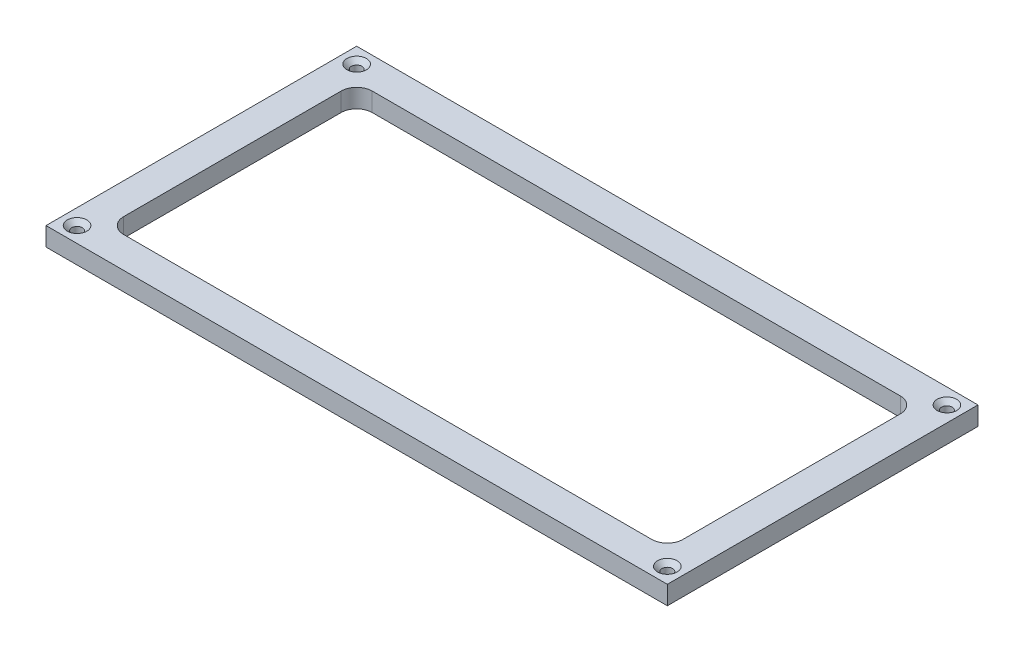
SolidWorks part; units mm, degrees
material "Pine"
ref_plane "Front Plane" through (0, 0, 0) normal (0, 0, 1) x (1, 0, 0)
ref_plane "Top Plane" through (0, 0, 0) normal (0, 1, 0) x (1, 0, 0)
ref_plane "Right Plane" through (0, 0, 0) normal (1, 0, 0) x (0, 0, -1)
sketch "Sketch1" plane through (0, 0, 0) normal (0, 1, 0) x (1, 0, 0)
  line L1 (0, 0) -> (200, 0)
  line L2 (0, 0) -> (0, 100)
  line L3 (0, 100) -> (200, 100)
  line L4 (200, 0) -> (200, 100)
  dimension "D1" = 200
  dimension "D2" = 100
extrude "Boss-Extrude1" add sketch "Sketch1" along normal blind 6
sketch "Sketch2" plane through (0, 6, 0) normal (0, 1, 0) x (1, 0, 0)
  line L0 (0, 100) -> (0, 0) construction
  line L1 (10, 90) -> (190, 90)
  line L2 (10, 90) -> (10, 10)
  line L3 (10, 10) -> (190, 10)
  line L4 (190, 90) -> (190, 10)
  line L5 (200, 0) -> (200, 100) construction
  line L6 (0, 0) -> (200, 0) construction
  line L7 (200, 100) -> (0, 100) construction
  point P6 (200, 50)
  dimension "D1" = 10
  dimension "D2" = 10
  dimension "D3" = 10
  dimension "D4" = 10
extrude "Cut-Extrude1" cut sketch "Sketch2" against normal through all
fillet "Fillet1" radius 5 4 edges at (10, 3, -10) (190, 3, -10) (190, 3, -90) (10, 3, -90)
hole_wizard "CSK for M3 Countersunk Flat Head Screw1" positions "Sketch4" profile "Sketch3" countersink size "M3" standard "DIN" end condition through all
sketch "Sketch4" plane through (0, 6, 0) normal (0, 1, 0) x (1, 0, 0)
  line L0 (0, 0) -> (200, 0) construction
  line L1 (0, 100) -> (0, 0) construction
  line L2 (200, 0) -> (200, 100) construction
  line L3 (200, 100) -> (0, 100) construction
  point P0 (5, 5)
  point P2 (5, 95)
  point P4 (195, 95)
  point P6 (195, 5)
  point P8 (5, 5)
  dimension "D1" = 5
  dimension "D2" = 5
  dimension "D3" = 5
  dimension "D4" = 5
sketch "Sketch3" plane through (5, 6, -5) normal (1, 0, 0) x (0, 0, 1)
  line L0 (0, 0) -> (0, 6)
  line L1 (0, 6) -> (1.7, 6)
  line L2 (1.7, 6) -> (1.7, 1.45)
  line L3 (1.7, 1.45) -> (3.15, 0)
  line L5 (3.15, 0) -> (0, 0)
  line L6 (-1.7, 1.45) -> (-3.15, 0) construction
  line L11 (0, -6.35) -> (0, 107.95) construction
  dimension "Thru Hole Dia." = 3.4
  dimension "Thru Hole Depth" = 6
  dimension "Near C'Sink Dia." = 6.3
  dimension "Near C'Sink Angle" = 90
equation "\"BoardThickness\"= 6"
equation "\"D1@Boss-Extrude1\"=\"BoardThickness\""
equation "\"D2@Sketch2\"=\"D1@Sketch2\""
equation "\"D3@Sketch2\"=\"D1@Sketch2\""
equation "\"D4@Sketch2\"=\"D1@Sketch2\""
